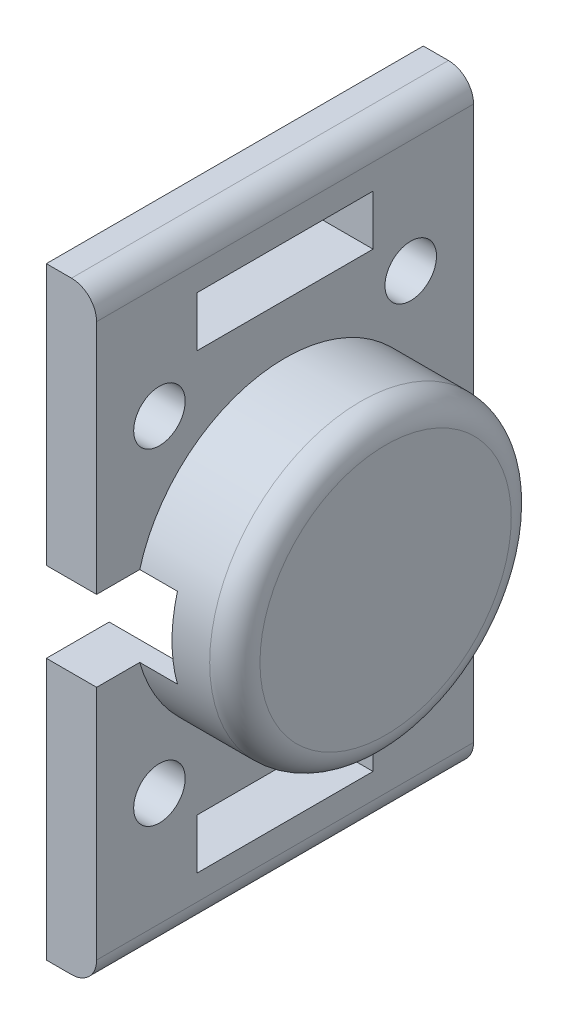
SolidWorks part; units mm, degrees
ref_plane "Front Plane" through (0, 0, 0) normal (0, 0, 1) x (1, 0, 0)
ref_plane "Top Plane" through (0, 0, 0) normal (0, 1, 0) x (1, 0, 0)
ref_plane "Right Plane" through (0, 0, 0) normal (1, 0, 0) x (0, 0, -1)
sketch "Sketch1" plane through (0, 0, -7.5) normal (-1, 0, 0) x (0, 0, 1)
  line L5 (-7.5, -12) -> (7.5, -12)
  line L6 (-7.5, -12) -> (-7.5, 12)
  line L7 (-7.5, 12) -> (7.5, 12)
  line L8 (7.5, -12) -> (7.5, 12)
  line L9 (-7.5, -12) -> (7.5, 12) construction
  line L10 (-7.5, 12) -> (7.5, -12) construction
  dimension "D1" = 15
  dimension "D2" = 24
extrude "Boss-Extrude1" add sketch "Sketch1" along normal blind 6
sketch "Sketch2" plane through (-6, 0, 0) normal (-1, 0, 0) x (0, 0, 1)
  circle A0 centre (-7.5, 0) radius 5.25
  dimension "D1" = 10.5
extrude "Cut-Extrude1" cut sketch "Sketch2" against normal blind 3.5
sketch "Sketch3" plane through (5, 0, 0) normal (0, 0, 1) x (1, 0, 0)
  line L16 (-11, 1.6) -> (-7.5, 1.6)
  line L17 (-11, 1.6) -> (-11, -1.6)
  line L22 (-11, -1.6) -> (-7.5, -1.6)
  line L23 (-7.5, 1.6) -> (-7.5, -1.6)
extrude "Cut-Extrude2" cut sketch "Sketch3" against normal up to next
sketch "Sketch4" plane through (0, 0, 0) normal (1, 0, 0) x (0, 0, -1)
  line L11 (4, 8) -> (11, 8)
  line L20 (4, 8) -> (4, 10)
  line L21 (4, 10) -> (11, 10)
  line L22 (11, 8) -> (11, 10)
  line L23 (4, -8) -> (11, -8)
  line L24 (4, -8) -> (4, -10)
  line L25 (4, -10) -> (11, -10)
  line L26 (11, -8) -> (11, -10)
extrude "Cut-Extrude3" cut sketch "Sketch4" against normal blind 10
sketch "Sketch5" plane through (-2.5, 0, 0) normal (-1, 0, 0) x (0, 0, 1)
  circle A0 centre (-7.5, 0) radius 0.8
  dimension "D1" = 1.6
extrude "Cut-Extrude4" cut sketch "Sketch5" against normal blind 1.2
sketch "Sketch6" plane through (0, 0, 0) normal (1, 0, 0) x (0, 0, -1)
  circle A0 centre (7.5, 0) radius 6
  dimension "D1" = 12
extrude "Cut-Extrude5" cut sketch "Sketch6" against normal blind 4 flip side to cut
hole_wizard "M2.5x0.45 Tapped Hole1" positions "Sketch7" profile "Sketch8" tap size "M2.5x0.45" standard "JIS"
sketch "Sketch7" plane through (-6, 0, 0) normal (-1, 0, 0) x (0, 0, 1)
  point P0 (-12.5, 6.5)
  point P2 (-2.5, 6.5)
  point P4 (-2.5, -6.5)
  point P6 (-12.5, -6.5)
  point P9 (0, 0)
  point P10 (0, 0)
  point P11 (0, 0)
  point P12 (0, 0)
sketch "Sketch8" plane through (-6, 6.5, -12.5) normal (0, 1, 0) x (0, 0, 1)
  line L0 (0, 0) -> (0, 6.9659)
  line L1 (0, 6.9659) -> (1.025, 6.35)
  line L2 (1.025, 6.35) -> (1.025, 0)
  line L5 (1.025, 0) -> (0, 0)
  line L10 (0, 6.9659) -> (-1.025, 6.35) construction
  line L11 (0, -6.35) -> (0, 107.95) construction
  dimension "Tap Drill Dia." = 2.05
  dimension "Tap Drill Depth" = 6.35
  dimension "Drill Angle" = 118
cosmetic thread "Hole Thread1" parameters "D1"=5, "D2"=2.5
cosmetic thread "Hole Thread2" parameters "D1"=5, "D2"=2.5
cosmetic thread "Hole Thread3" parameters "D1"=5, "D2"=2.5
cosmetic thread "Hole Thread4" parameters "D1"=5, "D2"=2.5
fillet "Fillet1" radius 1 3 edges at (0, 0, -13.5) (-4, -12, -7.5) (-4, 12, -7.5)
